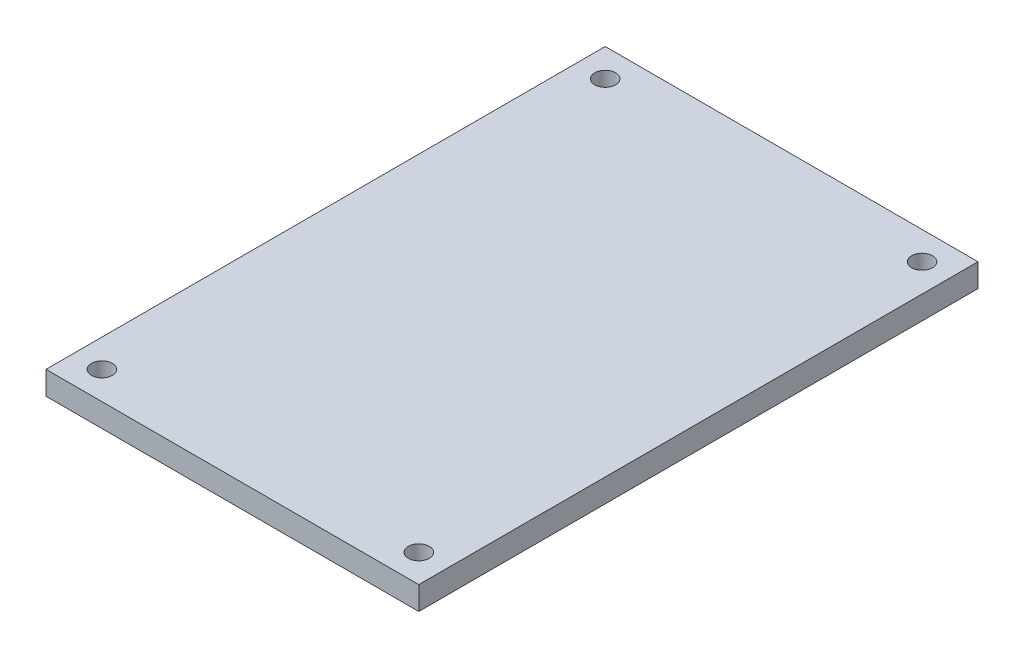
SolidWorks part; units mm, degrees
ref_plane "Front Plane" through (0, 0, 0) normal (0, 0, 1) x (1, 0, 0)
ref_plane "Top Plane" through (0, 0, 0) normal (0, 1, 0) x (1, 0, 0)
ref_plane "Right Plane" through (0, 0, 0) normal (1, 0, 0) x (0, 0, -1)
sketch "Sketch1" plane through (0, 0, 0) normal (0, 1, 0) x (1, 0, 0)
  line L0 (25.4, 76.2) -> (25.4, 0) construction
  line L1 (0, 0) -> (50.8, 0)
  line L2 (0, 0) -> (0, 76.2)
  line L3 (0, 76.2) -> (50.8, 76.2)
  line L4 (50.8, 0) -> (50.8, 76.2)
  line L5 (0, 38.1) -> (50.8, 38.1) construction
  circle A0 centre (3.81, 3.81) radius 1.4224
  circle A1 centre (3.81, 72.39) radius 1.4224
  circle A2 centre (46.99, 3.81) radius 1.4224
  circle A3 centre (46.99, 72.39) radius 1.4224
  point P11 (0, 0)
  point P13 (3.0742, 0)
  dimension "D3" = 3.81
  dimension "D1" = 76.2
  dimension "D2" = 50.8
  dimension "D4" = 3.81
extrude "Boss-Extrude1" add sketch "Sketch1" along normal blind 3.175
